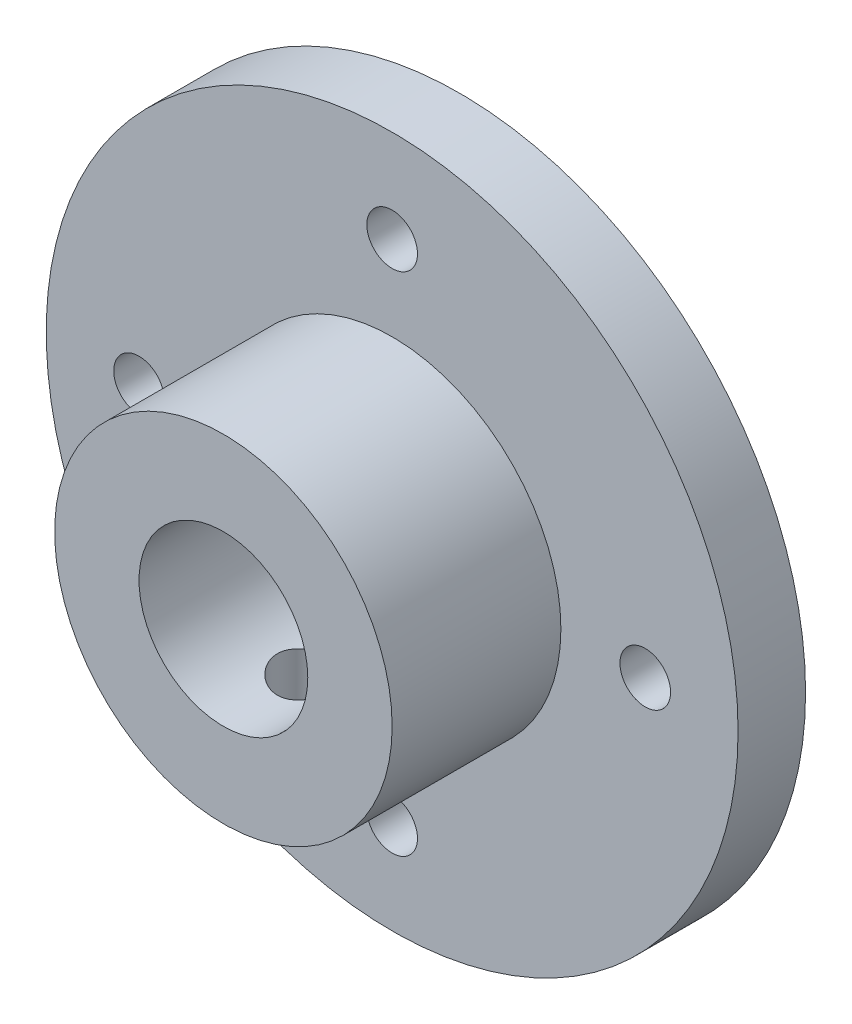
SolidWorks part; units mm, degrees
ref_plane "前视基准面" through (0, 0, 0) normal (0, 0, 1) x (1, 0, 0)
ref_plane "上视基准面" through (0, 0, 0) normal (0, 1, 0) x (1, 0, 0)
ref_plane "右视基准面" through (0, 0, 0) normal (1, 0, 0) x (0, 0, -1)
sketch "草图1" plane through (0, 0, 0) normal (0, 0, 1) x (1, 0, 0)
  arc A0 (1.5, 15) -> (-1.5, 15) centre (0, 15) ccw construction
  arc A1 (-1.5, 15) -> (1.5, 15) centre (0, 15) ccw construction
  arc A2 (-20.5, 0) -> (20.5, 0) centre (0, 0) ccw
  arc A3 (20.5, 0) -> (-20.5, 0) centre (0, 0) ccw
  arc A4 (-20.5, 0) -> (20.5, 0) centre (0, 0) ccw
  arc A5 (20.5, 0) -> (-20.5, 0) centre (0, 0) ccw
  arc A6 (16.5, 0) -> (13.5, 0) centre (15, 0) ccw construction
  arc A7 (13.5, 0) -> (16.5, 0) centre (15, 0) ccw construction
  arc A8 (1.5, -15) -> (-1.5, -15) centre (0, -15) ccw construction
  arc A9 (-1.5, -15) -> (1.5, -15) centre (0, -15) ccw construction
  arc A10 (-13.5, 0) -> (-16.5, 0) centre (-15, 0) ccw construction
  arc A11 (-16.5, 0) -> (-13.5, 0) centre (-15, 0) ccw construction
  arc A12 (-16.5, 0) -> (-13.5, 0) centre (-15, 0) ccw
  arc A13 (-13.5, 0) -> (-16.5, 0) centre (-15, 0) ccw
  arc A14 (-1.5, -15) -> (1.5, -15) centre (0, -15) ccw
  arc A15 (1.5, -15) -> (-1.5, -15) centre (0, -15) ccw
  arc A16 (13.5, 0) -> (16.5, 0) centre (15, 0) ccw
  arc A17 (16.5, 0) -> (13.5, 0) centre (15, 0) ccw
  arc A18 (-1.5, 15) -> (1.5, 15) centre (0, 15) ccw
  arc A19 (1.5, 15) -> (-1.5, 15) centre (0, 15) ccw
  arc A20 (-5, 0) -> (5, 0) centre (0, 0) ccw construction
  arc A21 (5, 0) -> (-5, 0) centre (0, 0) ccw construction
  arc A22 (-5, 0) -> (5, 0) centre (0, 0) ccw
  arc A23 (5, 0) -> (-5, 0) centre (0, 0) ccw
  dimension "D1" = 0
extrude "凸台-拉伸1" add sketch "草图1" along normal blind 4
sketch "草图2" plane through (0, 0, 4) normal (0, 0, 1) x (1, 0, 0)
  circle A0 centre (0, 0) radius 5
  circle A1 centre (0, 0) radius 10
  dimension "D1" = 20
extrude "凸台-拉伸2" add sketch "草图2" along normal blind 10
sketch "草图3" plane through (0, 0, 0) normal (0, 1, 0) x (1, 0, 0)
  line L0 (0, -9) -> (0, 0) construction
  circle A0 centre (0, -9) radius 1.8
  dimension "D2" = 3.6
  dimension "D1" = 9
extrude "切除-拉伸1" cut sketch "草图3" against normal blind 13
